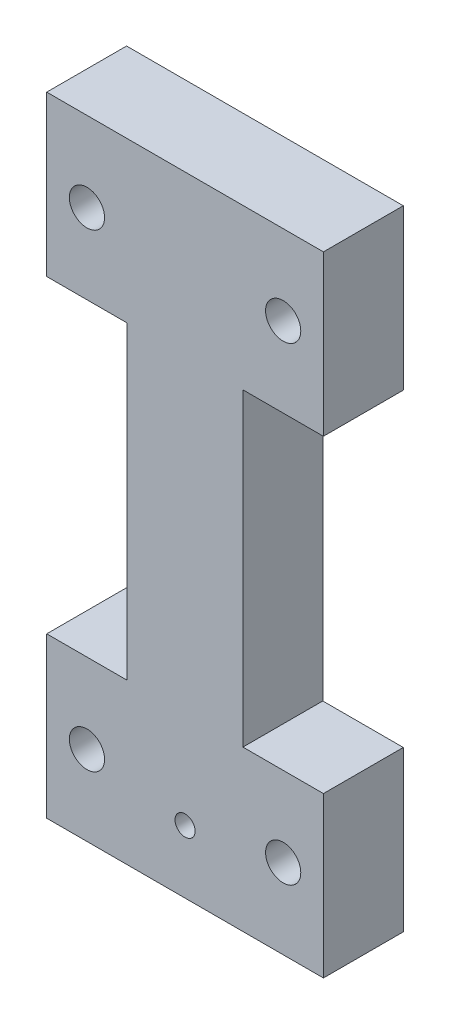
SolidWorks part; units mm, degrees
ref_plane "Front Plane" through (0, 0, 0) normal (0, 0, 1) x (1, 0, 0)
ref_plane "Top Plane" through (0, 0, 0) normal (0, 1, 0) x (1, 0, 0)
ref_plane "Right Plane" through (0, 0, 0) normal (1, 0, 0) x (0, 0, -1)
sketch "Sketch1" plane through (0, 0, 0) normal (0, 0, 1) x (1, 0, 0)
  line L1 (4.6, -25) -> (-4.6, -25)
  line L2 (4.6, -25) -> (4.6, 25)
  line L3 (4.6, 25) -> (-4.6, 25)
  line L4 (-4.6, -25) -> (-4.6, 25)
  line L5 (4.6, -25) -> (-4.6, 25) construction
  line L6 (4.6, 25) -> (-4.6, -25) construction
  line L7 (-4.6, 25) -> (-11, 25)
  line L9 (-4.6, 12.3) -> (-11, 12.3)
  line L10 (-11, 25) -> (-11, 12.3)
  line L11 (4.6, 25) -> (11, 25)
  line L13 (4.6, 12.3) -> (11, 12.3)
  line L14 (11, 25) -> (11, 12.3)
  line L15 (4.6, -25) -> (11, -25)
  line L17 (4.6, -12.3) -> (11, -12.3)
  line L18 (11, -25) -> (11, -12.3)
  line L19 (-4.6, -25) -> (-11, -25)
  line L21 (-4.6, -12.3) -> (-11, -12.3)
  line L22 (-11, -25) -> (-11, -12.3)
  circle A0 centre (-7.8, -18.65) radius 1.4
  circle A1 centre (-7.8, 18.65) radius 1.4
  circle A2 centre (7.8, 18.65) radius 1.4
  circle A3 centre (7.8, -18.65) radius 1.4
  point P0 (0, 0)
  point P20 (-7.8, 25)
  point P21 (7.8, 25)
  point P22 (-11, 18.65)
  point P23 (-11, -18.65)
  dimension "D7" = 2.8
  dimension "D1" = 50
  dimension "D2" = 12.7
  dimension "D3" = 22
  dimension "D4" = 6.4
extrude "Boss-Extrude1" add sketch "Sketch1" along normal blind 6.35
sketch "Sketch2" plane through (0, 0, 6.35) normal (0, 0, 1) x (1, 0, 0)
  line L1 (-11, -25) -> (11, -25) construction
  circle A0 centre (0, -20) radius 0.8
  dimension "D1" = 1.6
  dimension "D2" = 5
extrude "Cut-Extrude1" cut sketch "Sketch2" against normal through all
